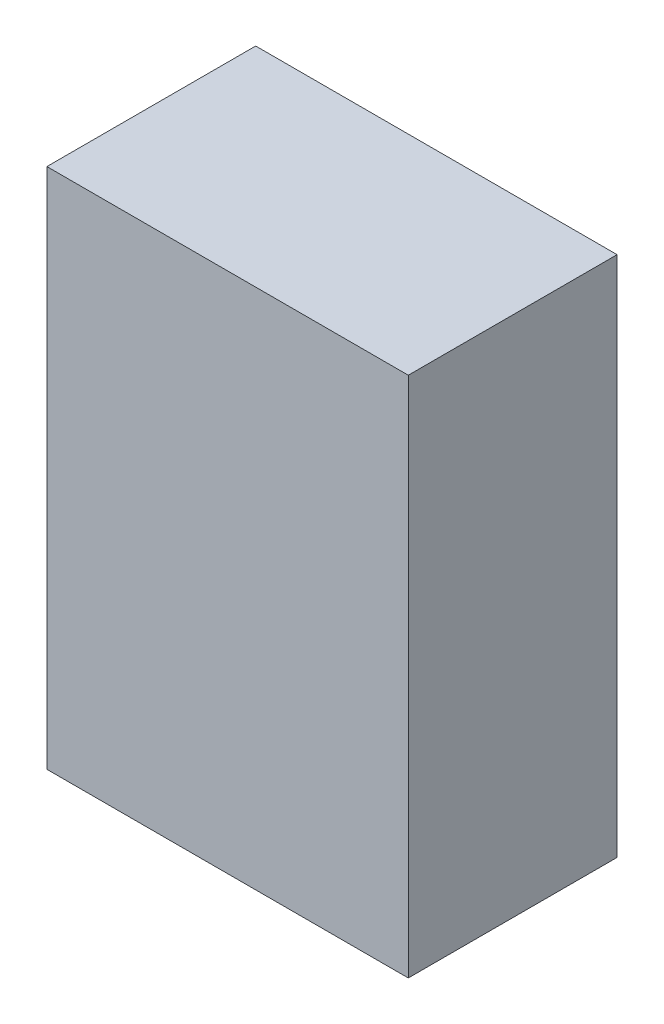
SolidWorks part; units mm, degrees
material "Brass"
ref_plane "Front Plane" through (0, 0, 0) normal (0, 0, 1) x (1, 0, 0)
ref_plane "Top Plane" through (0, 0, 0) normal (0, 1, 0) x (1, 0, 0)
ref_plane "Right Plane" through (0, 0, 0) normal (1, 0, 0) x (0, 0, -1)
sketch "Sketch1" plane through (0, 0, 0) normal (0, 0, 1) x (1, 0, 0)
  line L1 (0, 0) -> (45, 0)
  line L2 (0, 0) -> (0, 65)
  line L3 (0, 65) -> (45, 65)
  line L4 (45, 0) -> (45, 65)
  dimension "D1" = 45
  dimension "D2" = 65
extrude "Boss-Extrude1" add sketch "Sketch1" along normal blind 26
